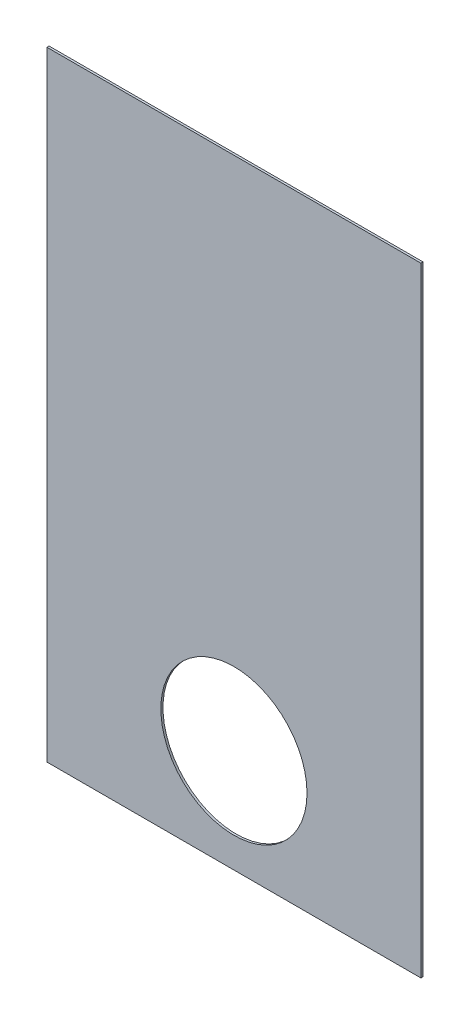
SolidWorks part; units mm, degrees
material "PMMA"
ref_plane "Front Plane" through (0, 0, 0) normal (0, 0, 1) x (1, 0, 0)
ref_plane "Top Plane" through (0, 0, 0) normal (0, 1, 0) x (1, 0, 0)
ref_plane "Right Plane" through (0, 0, 0) normal (1, 0, 0) x (0, 0, -1)
sketch "Sketch1" plane through (0, 0, 0) normal (0, 0, 1) x (1, 0, 0)
  line L1 (-276.225, 457.2) -> (276.225, 457.2)
  line L2 (-276.225, 457.2) -> (-276.225, -457.2)
  line L3 (-276.225, -457.2) -> (276.225, -457.2)
  line L4 (276.225, 457.2) -> (276.225, -457.2)
  line L5 (-276.225, 457.2) -> (276.225, -457.2) construction
  line L6 (-276.225, -457.2) -> (276.225, 457.2) construction
  point P0 (0, 0)
  dimension "D1" = 552.45
  dimension "D2" = 914.4
extrude "Boss-Extrude1" add sketch "Sketch1" along normal blind 3.175
sketch "Sketch2" plane through (0, 0, 3.175) normal (0, 0, 1) x (1, 0, 0)
  line L1 (-276.225, 457.2) -> (-276.225, -457.2) construction
  circle A0 centre (0, -304.8) radius 107.95
  dimension "D1" = 215.9
  dimension "D2" = 304.8
  dimension "D3" = 276.225
extrude "Cut-Extrude1" cut sketch "Sketch2" against normal blind 5.08
